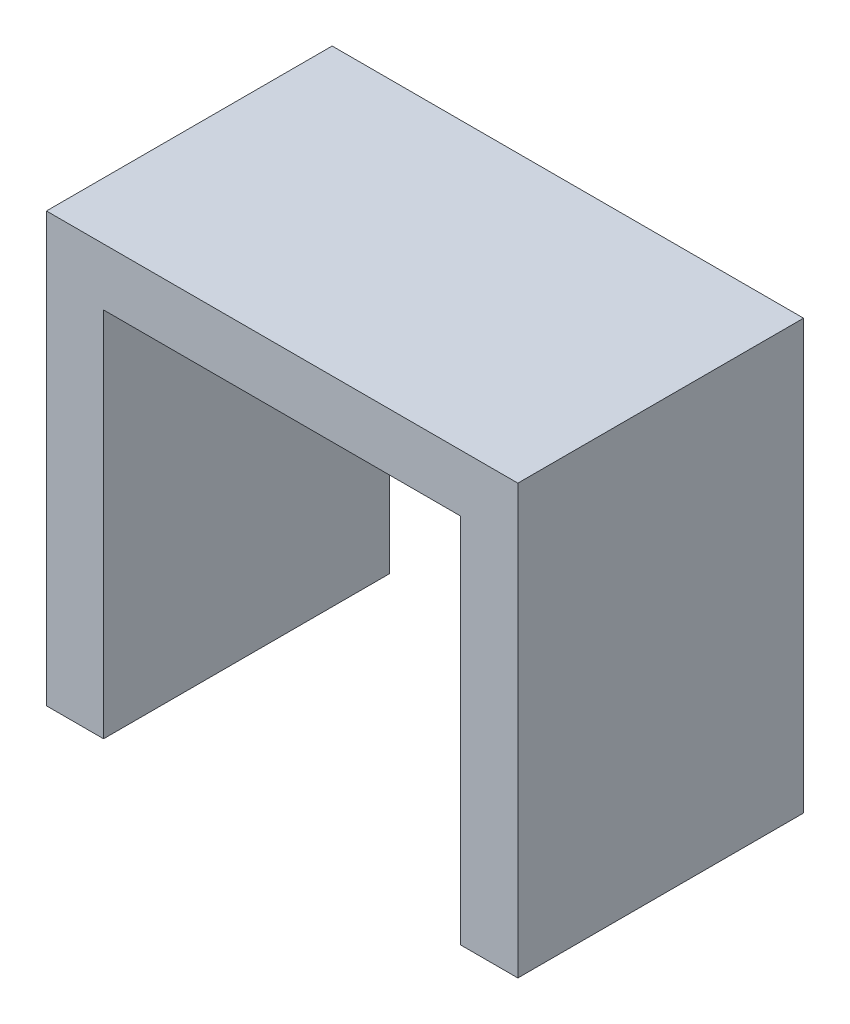
SolidWorks part; units mm, degrees
ref_plane "Front Plane" through (0, 0, 0) normal (0, 0, 1) x (1, 0, 0)
ref_plane "Top Plane" through (0, 0, 0) normal (0, 1, 0) x (1, 0, 0)
ref_plane "Right Plane" through (0, 0, 0) normal (1, 0, 0) x (0, 0, -1)
sketch "Sketch1" plane through (0, 0, 0) normal (0, 0, 1) x (1, 0, 0)
  line L0 (-12.5988, 0) -> (-10.5988, 0)
  line L1 (-10.5988, 0) -> (-10.5988, 13)
  line L2 (-10.5988, 13) -> (1.9012, 13)
  line L3 (1.9012, 13) -> (1.9012, 0)
  line L4 (1.9012, 0) -> (3.9012, 0)
  line L5 (3.9012, 0) -> (3.9012, 15)
  line L6 (3.9012, 15) -> (-12.5988, 15)
  line L7 (-12.5988, 15) -> (-12.5988, 0)
  dimension "D1" = 12.5
  dimension "D3" = 2
  dimension "D6" = 13
  dimension "D7" = 2
extrude "Boss-Extrude1" add sketch "Sketch1" along normal blind 10
